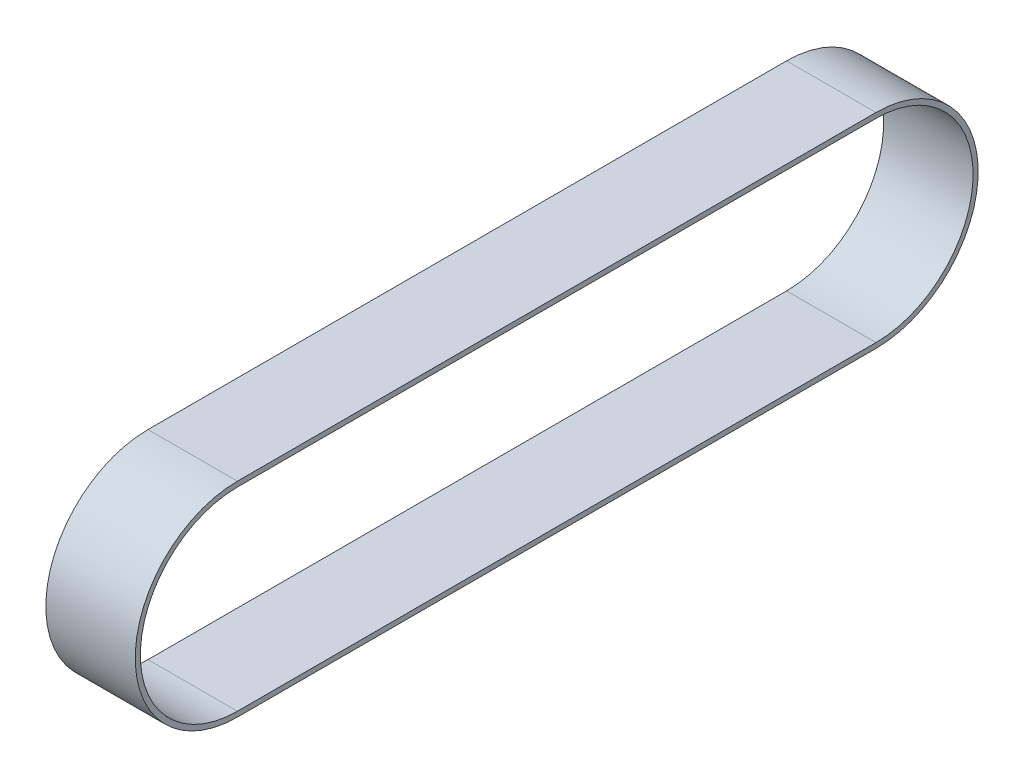
SolidWorks part; units mm, degrees
ref_plane "Front Plane" through (0, 0, 0) normal (0, 0, 1) x (1, 0, 0)
ref_plane "Top Plane" through (0, 0, 0) normal (0, 1, 0) x (1, 0, 0)
ref_plane "Right Plane" through (0, 0, 0) normal (1, 0, 0) x (0, 0, -1)
sketch "Sketch1" plane through (0, 0, 0) normal (1, 0, 0) x (0, 0, -1)
  line L0 (0, 0) -> (-250, 0) construction
  line L1 (0, -40) -> (-250, -40)
  line L2 (0, 40) -> (-250, 40)
  line L3 (0, -38) -> (-250, -38)
  line L4 (0, 38) -> (-250, 38)
  arc A0 (0, -40) -> (0, 40) centre (0, 0) ccw
  arc A1 (-250, 40) -> (-250, -40) centre (-250, 0) ccw
  arc A2 (-250, 38) -> (-250, -38) centre (-250, 0) ccw
  arc A3 (0, -38) -> (0, 38) centre (0, 0) ccw
  point P3 (-125, 0)
  dimension "D2" = 40
  dimension "D1" = 250
  dimension "D3" = 2
extrude "Boss-Extrude1" add sketch "Sketch1" along normal blind 35
